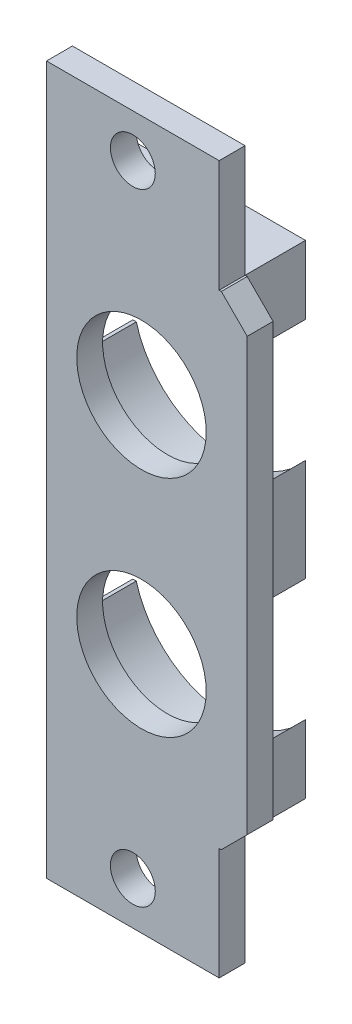
SolidWorks part; units mm, degrees
material "PET"
ref_plane "Front Plane" through (0, 0, 0) normal (0, 0, 1) x (1, 0, 0)
ref_plane "Top Plane" through (0, 0, 0) normal (0, 1, 0) x (1, 0, 0)
ref_plane "Right Plane" through (0, 0, 0) normal (1, 0, 0) x (0, 0, -1)
sketch "Sketch9" plane through (0, 0, 0) normal (0, 0, 1) x (1, 0, 0)
  line L0 (10, 31) -> (-10, -31) construction
  line L1 (10, 31) -> (-10, 31)
  line L2 (10, 31) -> (10, 20.0711)
  line L3 (10, -31) -> (-10, -31)
  line L4 (-10, 31) -> (-10, 15.9732)
  line L5 (10, -31) -> (-10, -41) construction
  line L6 (10, -31) -> (-10, -31)
  line L7 (10, -31) -> (10, -41)
  line L8 (10, -41) -> (-10, -41)
  line L9 (-10, -31) -> (-10, -41)
  line L10 (-10, 31) -> (10, 31)
  line L11 (-10, 31) -> (-10, 41)
  line L12 (-10, 41) -> (10, 41)
  line L13 (10, 31) -> (10, 41)
  line L14 (10, 41) -> (-10, 31) construction
  line L16 (10, 5.9289) -> (10, -5.9289)
  line L17 (10, -20.0711) -> (10, -31)
  line L18 (-9.6, 15.9732) -> (-10, 15.9732)
  line L19 (-9.6, 10.0268) -> (-10, 10.0268)
  line L20 (-10, 10.0268) -> (-10, -10.0268)
  line L21 (-9.6, -10.0268) -> (-10, -10.0268)
  line L22 (-9.6, -15.9732) -> (-10, -15.9732)
  line L23 (-10, -15.9732) -> (-10, -31)
  line L24 (-10, 31) -> (10, 31)
  line L25 (-10, 31) -> (-10, 28)
  line L26 (-10, 28) -> (10, 28)
  line L27 (10, 31) -> (10, 28)
  line L28 (-10, -31) -> (10, -31)
  line L29 (-10, -31) -> (-10, -28)
  line L30 (-10, -28) -> (10, -28)
  line L31 (10, -31) -> (10, -28)
  circle A0 centre (0, -36) radius 2.6
  circle A1 centre (0, 36) radius 2.6
  arc A2 (10, 20.0711) -> (-9.6, 15.9732) centre (1.25, 13) ccw
  arc A3 (10, -5.9289) -> (-9.6, -10.0268) centre (1.25, -13) ccw
  arc A4 (-9.6, 10.0268) -> (10, 5.9289) centre (1.25, 13) ccw
  arc A5 (-9.6, -15.9732) -> (10, -20.0711) centre (1.25, -13) ccw
  point P4 (0, 0)
  point P15 (0, -36)
  point P17 (0, 36)
  dimension "D2" = 5.2
  dimension "D3" = 5.2
  dimension "D6" = 22.5
  dimension "D7" = 22.5
  dimension "D9" = 18
  dimension "D1" = 20
  dimension "D4" = 10
  dimension "D5" = 10
  dimension "D8" = 18
  dimension "D10" = 26
  dimension "D11" = 0.4
  dimension "D12" = 0.4
  dimension "D13" = 0.4
  dimension "D14" = 0.4
  dimension "D15" = 3
  dimension "D16" = 3
sketch "Sketch10" plane through (0, 0, 0) normal (0, 0, 1) x (1, 0, 0)
  line L0 (10, 31) -> (-10, -31) construction
  line L1 (10, 31) -> (-10, 31)
  line L2 (10, 31) -> (10, 19.3246)
  line L3 (10, -31) -> (-10, -31)
  line L4 (-10, 31) -> (-10, 15.1012)
  line L5 (10, -31) -> (-10, -41) construction
  line L6 (10, -31) -> (-10, -31)
  line L7 (10, -31) -> (10, -41)
  line L8 (10, -41) -> (-10, -41)
  line L9 (-10, -31) -> (-10, -41)
  line L10 (-10, 31) -> (10, 31)
  line L11 (-10, 31) -> (-10, 41)
  line L12 (-10, 41) -> (10, 41)
  line L13 (10, 31) -> (10, 41)
  line L14 (10, 41) -> (-10, 31) construction
  line L16 (10, 19.3246) -> (10, -17.4092)
  line L17 (10, -17.4092) -> (10, -31)
  line L20 (-10, 15.1012) -> (-10, -10.0606)
  line L23 (-10, -10.0606) -> (-10, -31)
  circle A0 centre (0, -36) radius 2.6
  circle A1 centre (0, 36) radius 2.6
  arc A2 (10, 19.3246) -> (7.1381, 22.1282) centre (1, 13) ccw
  circle A6 centre (1, 13) radius 7.5
  circle A7 centre (1, -13) radius 7.5
  point P4 (0, 0)
  point P15 (0, -36)
  point P17 (0, 36)
  dimension "D2" = 5.2
  dimension "D3" = 5.2
  dimension "D6" = 22
  dimension "D7" = 18
  dimension "D15" = 15
  dimension "D16" = 15
  dimension "D1" = 20
  dimension "D4" = 10
  dimension "D5" = 10
  dimension "D8" = 18
  dimension "D10" = 26
extrude "Boss-Extrude7" add sketch "Sketch10" against normal blind 3
extrude "Boss-Extrude10" add sketch "Sketch9" against normal offset from surface (10 mm away) 7 contours A4 L19 L20 L21 A3 L16 | A2 L2 L26 L4 L18 | A5 L22 L23 L30 L17 up to face at (2.6, 36, -3) offset beyond the face yes
sketch "Sketch12" plane through (0, 0, -3) normal (0, 0, -1) x (-1, 0, 0)
  line L0 (10, -28) -> (-10, -28) construction
  line L1 (-10, 28) -> (-13.25, 28)
  line L2 (-10, 28) -> (-10, -28)
  line L3 (-10, -28) -> (-13.25, -28)
  line L4 (-13.25, 28) -> (-13.25, -28)
  arc A0 (9.6, 15.9732) -> (-10, 20.0711) centre (-1.25, 13) ccw construction
  dimension "D1" = 12
extrude "Boss-Extrude11" add sketch "Sketch12" against normal blind 3
chamfer "Chamfer2" distance 3 angle 45 1 edges at (13.25, -28, -1.5)
chamfer "Chamfer3" distance 3 angle 45 1 edges at (13.25, 28, -1.5)
